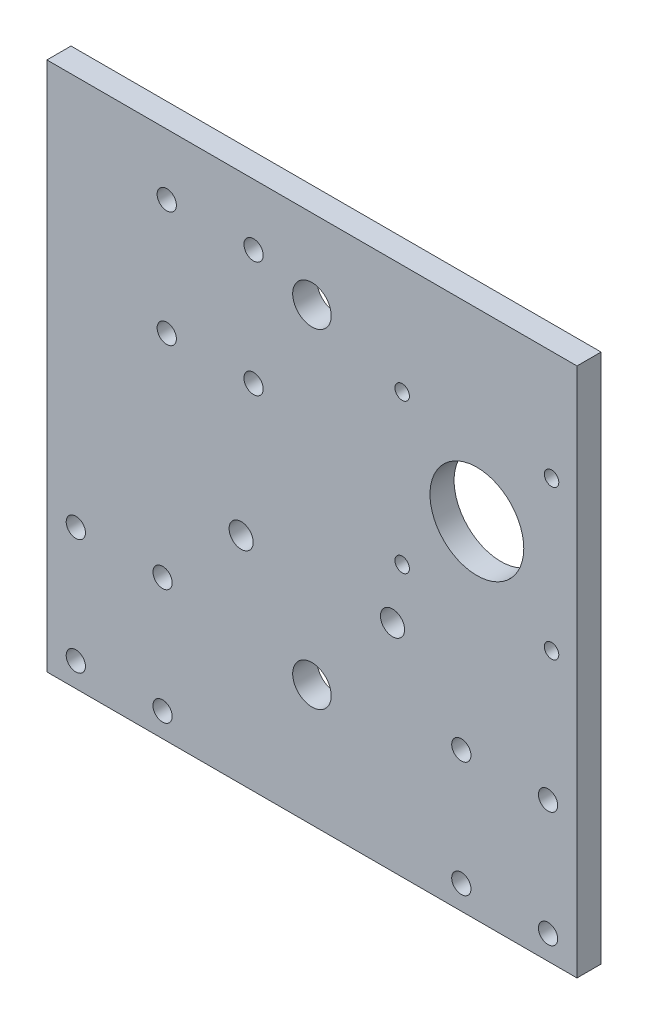
SolidWorks part; units mm, degrees
ref_plane "Front Plane" through (0, 0, 0) normal (0, 0, 1) x (1, 0, 0)
ref_plane "Top Plane" through (0, 0, 0) normal (0, 1, 0) x (1, 0, 0)
ref_plane "Right Plane" through (0, 0, 0) normal (1, 0, 0) x (0, 0, -1)
sketch "Sketch1" plane through (0, 0, 0) normal (0, 0, 1) x (1, 0, 0)
  line L0 (-49, -33.3512) -> (-31, -33.3512) construction
  line L1 (-55, 47.6488) -> (55, 47.6488)
  line L2 (-55, 47.6488) -> (-55, -62.3512)
  line L3 (-55, -62.3512) -> (55, -62.3512)
  line L4 (55, 47.6488) -> (55, -62.3512)
  line L5 (-31, -33.3512) -> (-31, -57.3512) construction
  line L6 (-31, -57.3512) -> (-49, -57.3512) construction
  line L19 (-49, -57.3512) -> (-49, -33.3512) construction
  line L20 (-31, -33.3512) -> (0, -33.3512) construction
  line L21 (31, -33.3512) -> (49, -33.3512) construction
  line L22 (49, -33.3512) -> (49, -57.3512) construction
  line L23 (49, -57.3512) -> (31, -57.3512) construction
  line L24 (31, -57.3512) -> (31, -33.3512) construction
  line L25 (0, 0) -> (0, -62.3512) construction
  line L26 (31, -33.3512) -> (0, -33.3512) construction
  line L27 (0, 0) -> (0, 47.6488) construction
  line L32 (18.7257, 24.8288) -> (49.7257, -6.1712) construction
  line L33 (18.7257, -6.1712) -> (49.7257, 24.8288) construction
  line L34 (-21.1236, 22.9488) -> (-31, -33.3512) construction
  line L39 (-30.1302, 34.9576) -> (-12.1171, 34.9576) construction
  line L44 (-14.693, -17.6564) -> (16.7207, -17.6564) construction
  line L46 (-12.1171, 34.9576) -> (-12.1171, 10.9401) construction
  line L47 (-12.1171, 10.9401) -> (-30.1302, 10.9401) construction
  line L48 (-30.1302, 10.9401) -> (-30.1302, 34.9576) construction
  line L49 (-30.1302, 34.9576) -> (-12.1171, 10.9401) construction
  line L50 (-12.1171, 34.9576) -> (-30.1302, 10.9401) construction
  line L54 (18.7257, 24.8288) -> (49.7257, 24.8288) construction
  line L55 (49.7257, 24.8288) -> (49.7257, -6.1712) construction
  line L56 (49.7257, -6.1712) -> (18.7257, -6.1712) construction
  line L57 (18.7257, -6.1712) -> (18.7257, 24.8288) construction
  circle A0 centre (-31, -33.3512) radius 2
  circle A1 centre (-49, -33.3512) radius 2
  circle A2 centre (-49, -57.3512) radius 2
  circle A3 centre (-31, -57.3512) radius 2
  circle A4 centre (49, -33.3512) radius 2
  circle A5 centre (31, -33.3512) radius 2
  circle A6 centre (31, -57.3512) radius 2
  circle A7 centre (49, -57.3512) radius 2
  circle A8 centre (34.2257, 9.3288) radius 9.7308
  circle A9 centre (49.7257, 24.8288) radius 1.5
  circle A10 centre (49.7257, -6.1712) radius 1.5
  circle A11 centre (18.7257, -6.1712) radius 1.5
  circle A12 centre (18.7257, 24.8288) radius 1.5
  circle A13 centre (0, 31.1488) radius 4
  circle A14 centre (0, -37.1512) radius 4
  circle A15 centre (-12.1171, 34.9576) radius 2
  circle A16 centre (-30.1302, 34.9576) radius 2
  circle A17 centre (-30.1302, 10.9401) radius 2
  circle A18 centre (-12.1171, 10.9401) radius 2
  circle A19 centre (16.7207, -17.6564) radius 2.5
  circle A20 centre (-14.693, -17.6564) radius 2.5
  point P0 (0, 0)
  point P12 (-40, -45.3512)
  point P25 (34.2257, 9.3288)
  point P42 (10.6097, -20.0706)
  point P43 (-25.7656, -19.7543)
  point P44 (-21.1236, -19.5434)
  point P51 (11.8188, -18.9997)
  point P52 (-14.693, -19.0647)
  point P53 (16.7207, -19.1753)
  dimension "D6" = 31
  dimension "D7" = 68.3
  dimension "D1" = 110
  dimension "D2" = 110
  dimension "D3" = 31
  dimension "D4" = 24
  dimension "D5" = 18
  dimension "D9" = 68.3
extrude "Boss-Extrude1" add sketch "Sketch1" along normal blind 5
